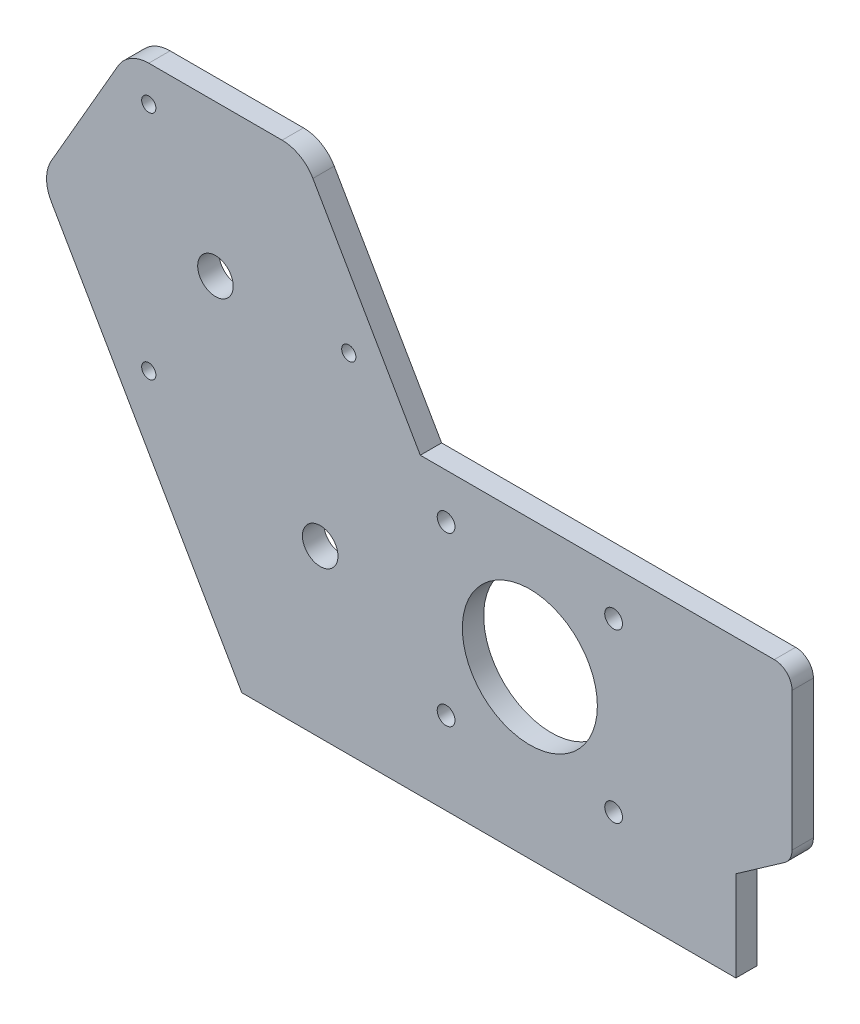
SolidWorks part; units mm, degrees
ref_plane "Front Plane" through (0, 0, 0) normal (0, 0, 1) x (1, 0, 0)
ref_plane "Top Plane" through (0, 0, 0) normal (0, 1, 0) x (1, 0, 0)
ref_plane "Right Plane" through (0, 0, 0) normal (1, 0, 0) x (0, 0, -1)
sketch "Sketch2" plane through (0, 0, 0) normal (0, 0, 1) x (1, 0, 0)
  line L8 (-69.0483, 22) -> (70, 22)
  line L9 (70, 22) -> (70, 47.4)
  line L10 (70, 47.4) -> (83.6679, 56.9704)
  line L11 (85.8, 61.0661) -> (85.8, 100)
  line L12 (-18.8188, 105) -> (80.8, 105)
  line L13 (-18.8188, 105) -> (-49.0405, 157.3455)
  line L14 (-57.7007, 162.3455) -> (-95.2285, 162.3455)
  line L15 (-103.8888, 157.3455) -> (-122.6526, 124.8455)
  line L17 (-122.6526, 114.8455) -> (-69.0483, 22)
  circle A15 centre (-11.5577, 45.22) radius 2.5
  circle A16 centre (35.5823, 45.22) radius 2.5
  circle A17 centre (35.5823, 92.36) radius 2.5
  circle A18 centre (12.0123, 68.79) radius 19
  circle A19 centre (-11.5577, 92.36) radius 2.5
  circle A20 centre (-46.9877, 68.79) radius 5
  circle A21 centre (-38.9369, 119.8455) radius 2
  circle A22 centre (-95.2285, 87.3455) radius 2
  circle A23 centre (-76.4646, 119.8455) radius 5
  circle A24 centre (-95.2285, 152.3455) radius 2
  arc A25 (83.6679, 56.9704) -> (85.8, 61.0661) centre (80.8, 61.0661) ccw
  arc A26 (85.8, 100) -> (80.8, 105) centre (80.8, 100) ccw
  arc A27 (-49.0405, 157.3455) -> (-57.7007, 162.3455) centre (-57.7007, 152.3455) ccw
  arc A28 (-95.2285, 162.3455) -> (-103.8888, 157.3455) centre (-95.2285, 152.3455) ccw
  arc A29 (-122.6526, 124.8455) -> (-122.6526, 114.8455) centre (-113.9924, 119.8455) ccw
  point P1 (0, 0)
  point P3 (0, 0)
  point P5 (0, 0)
  point P7 (0, 0)
  point P9 (0, 0)
  point P11 (-73.9885, 119.0108)
  point P13 (-95.9257, 152.167)
  point P17 (-118.8095, 131.5021)
  dimension "D1" = 10
  dimension "D15" = 5
  dimension "D24" = 5
  dimension "D25" = 38
  dimension "D28" = 10
  dimension "D29" = 10
  dimension "D30" = 4
  dimension "D31" = 42.5
  dimension "D2" = 90
  dimension "D3" = 4.6175
  dimension "D4" = 38.9339
  dimension "D5" = 25.4
  dimension "D6" = 16.6854
  dimension "D7" = 99.6188
  dimension "D8" = 139.0483
  dimension "D9" = 107.2087
  dimension "D10" = 60.4434
  dimension "D11" = 37.5278
  dimension "D12" = 22
  dimension "D13" = 70
  dimension "D14" = 120
  dimension "D16" = 60
  dimension "D17" = 60
  dimension "D18" = 47.14
  dimension "D19" = 47.14
  dimension "D20" = 47.14
  dimension "D21" = 47.14
  dimension "D22" = 23.57
  dimension "D23" = 23.57
  dimension "D26" = 46.79
  dimension "D27" = 57.9877
  dimension "D32" = 65
  dimension "D33" = 65
  dimension "D34" = 65
  dimension "D35" = 37.5278
  dimension "D36" = 37.5278
  dimension "D37" = 42.5
  dimension "D39" = 46.79
  dimension "D40" = 42.5
extrude "Boss-Extrude2" add sketch "Sketch2" along normal blind 6 separate body
